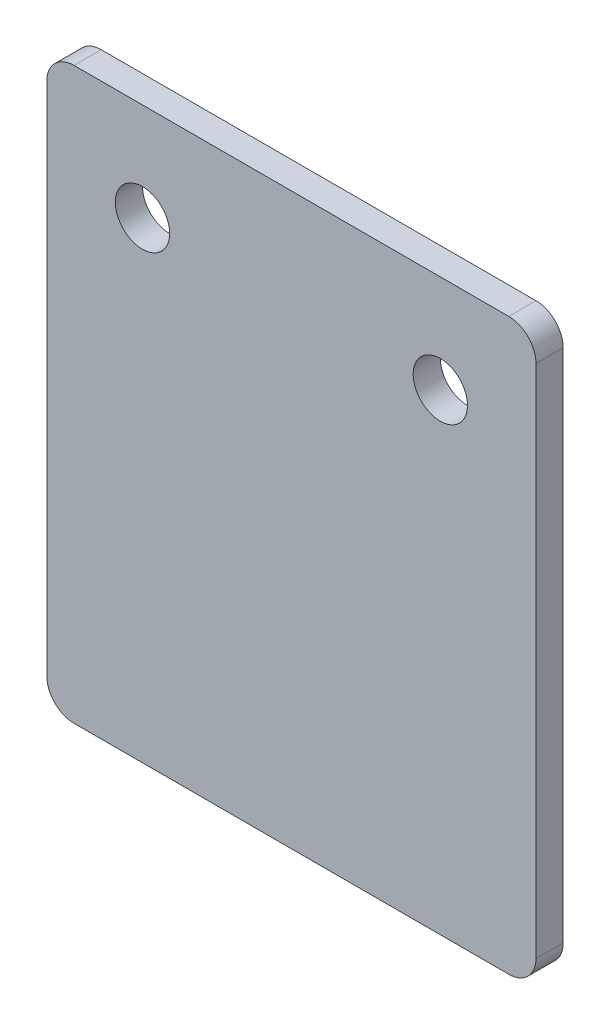
SolidWorks part; units mm, degrees
material "AISI 4130 Steel, annealed at 865C"
ref_plane "X-Y Datum" through (0, 0, 0) normal (0, 0, 1) x (1, 0, 0)
ref_plane "X-Z Datum" through (0, 0, 0) normal (0, 1, 0) x (1, 0, 0)
ref_plane "Y-Z Datum" through (0, 0, 0) normal (1, 0, 0) x (0, 0, -1)
sketch "Sketch1" plane through (0, 0, 0) normal (0, 0, 1) x (1, 0, 0)
  line L1 (-28.329, 3.0708) -> (-28.329, -34.9225)
  line L3 (28.821, -34.9225) -> (28.821, 3.0708)
  line L4 (-25.154, 6.2458) -> (25.646, 6.2458)
  line L5 (0, 0) -> (-28.329, 0) construction
  line L6 (-28.329, -34.9225) -> (-28.329, -57.1475)
  line L7 (28.821, -34.9225) -> (28.821, -57.1475)
  line L8 (-25.154, -60.3225) -> (25.646, -60.3225)
  line L9 (0, 0) -> (0, 6.2458) construction
  line L10 (0, 0) -> (0.246, -60.3225) construction
  arc A2 (25.646, 6.2458) -> (28.821, 3.0708) centre (25.646, 3.0708) cw
  arc A3 (-25.154, 6.2458) -> (-28.329, 3.0708) centre (-25.154, 3.0708) ccw
  arc A4 (28.821, -57.1475) -> (25.646, -60.3225) centre (25.646, -57.1475) cw
  arc A5 (-28.329, -57.1475) -> (-25.154, -60.3225) centre (-25.154, -57.1475) ccw
  point P4 (0, 0)
  point P10 (28.821, -60.3225)
  dimension "D1" = 25.4
  dimension "D4" = 3.175
  dimension "D2" = 57.15
  dimension "D3" = 37.9932
  dimension "D5" = 28.329
  dimension "D6" = 6.2458
  dimension "D7" = 60.3225
extrude "Boss-Extrude1" add sketch "Sketch1" against normal blind 3.175
sketch "Sketch2" plane through (0, 0, 0) normal (0, 0, 1) x (1, 0, 0)
  line L0 (0.246, -60.3225) -> (0.246, 6.2458) construction
  line L2 (-25.154, -60.3225) -> (25.646, -60.3225) construction
  line L3 (-17.153, -5.1842) -> (-17.153, 6.2458) construction
  line L4 (25.646, 6.2458) -> (-25.154, 6.2458) construction
  line L5 (-28.329, -5.1842) -> (-17.153, -5.1842) construction
  line L6 (-28.329, 3.0708) -> (-28.329, -57.1475) construction
  line L7 (-25.154, -60.3225) -> (25.646, -60.3225) construction
  circle A0 centre (-17.153, -5.1842) radius 3.175
  circle A1 centre (17.645, -5.1842) radius 3.175
  dimension "D1" = 11.176
  dimension "D3" = 6.35
  dimension "D2" = 11.43
extrude "Cut-Extrude1" cut sketch "Sketch2" against normal through all
